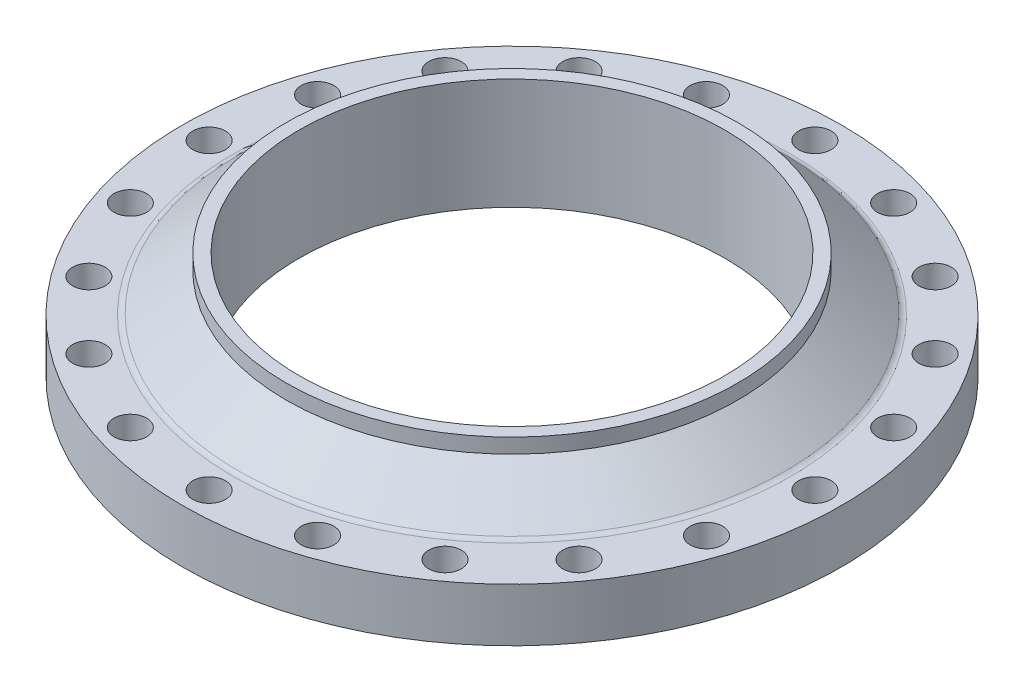
SolidWorks part; units mm, degrees
ref_plane "Front Plane" through (0, 0, 0) normal (0, 0, 1) x (1, 0, 0)
ref_plane "Top Plane" through (0, 0, 0) normal (0, 1, 0) x (1, 0, 0)
ref_plane "Right Plane" through (0, 0, 0) normal (1, 0, 0) x (0, 0, -1)
sketch "Sketch1" plane through (0, 0, 0) normal (0, 0, 1) x (1, 0, 0)
  line L0 (0, 0) -> (0, 180.5412) construction
  line L8 (287.4, 50.8119) -> (287.4, 200.8119)
  line L9 (287.4, 200.8119) -> (304.8, 200.8119)
  line L11 (376.7688, 127.8119) -> (445, 127.8119)
  line L12 (445, 127.8119) -> (445, 55.8119)
  line L13 (445, 55.8119) -> (375, 55.8119)
  line L14 (375, 55.8119) -> (370, 50.8119)
  line L15 (370, 50.8119) -> (287.4, 50.8119)
  line L17 (304.8, 200.8119) -> (304.8, 180.8119)
  line L18 (304.8, 180.8119) -> (369.3809, 130.3558)
  arc A0 (369.3809, 130.3558) -> (376.7688, 127.8119) centre (376.7688, 139.8119) ccw
  point P14 (372.6369, 127.8119)
  dimension "D13" = 12
  dimension "D1" = 150
  dimension "D2" = 72
  dimension "D3" = 17.4
  dimension "D4" = 287.4
  dimension "D5" = 445
  dimension "D6" = 20
  dimension "D7" = 128
  dimension "D8" = 5
  dimension "D9" = 135
  dimension "D10" = 82.6
  dimension "D11" = 72.3631
  dimension "D12" = 142
revolve "Revolve1" add sketch "Sketch1" angle 360 about L0
sketch "Sketch2" plane through (0, 55.8119, 0) normal (0, -1, 0) x (1, 0, 0)
  circle A0 centre (0, 0) radius 409 construction
  circle A1 centre (0, 409) radius 22
  circle A2 centre (126.388, 388.9821) radius 22
  circle A3 centre (240.4042, 330.888) radius 22
  circle A4 centre (330.888, 240.4042) radius 22
  circle A5 centre (388.9821, 126.388) radius 22
  circle A6 centre (409, 0) radius 22
  circle A7 centre (388.9821, -126.388) radius 22
  circle A8 centre (330.888, -240.4042) radius 22
  circle A9 centre (240.4042, -330.888) radius 22
  circle A10 centre (126.388, -388.9821) radius 22
  circle A11 centre (0, -409) radius 22
  circle A12 centre (-126.388, -388.9821) radius 22
  circle A13 centre (-240.4042, -330.888) radius 22
  circle A14 centre (-330.888, -240.4042) radius 22
  circle A15 centre (-388.9821, -126.388) radius 22
  circle A16 centre (-409, 0) radius 22
  circle A17 centre (-388.9821, 126.388) radius 22
  circle A18 centre (-330.888, 240.4042) radius 22
  circle A19 centre (-240.4042, 330.888) radius 22
  circle A20 centre (-126.388, 388.9821) radius 22
  point P46 (0, 0)
  dimension "D1" = 20
extrude "Cut-Extrude1" cut sketch "Sketch2" against normal up to next
